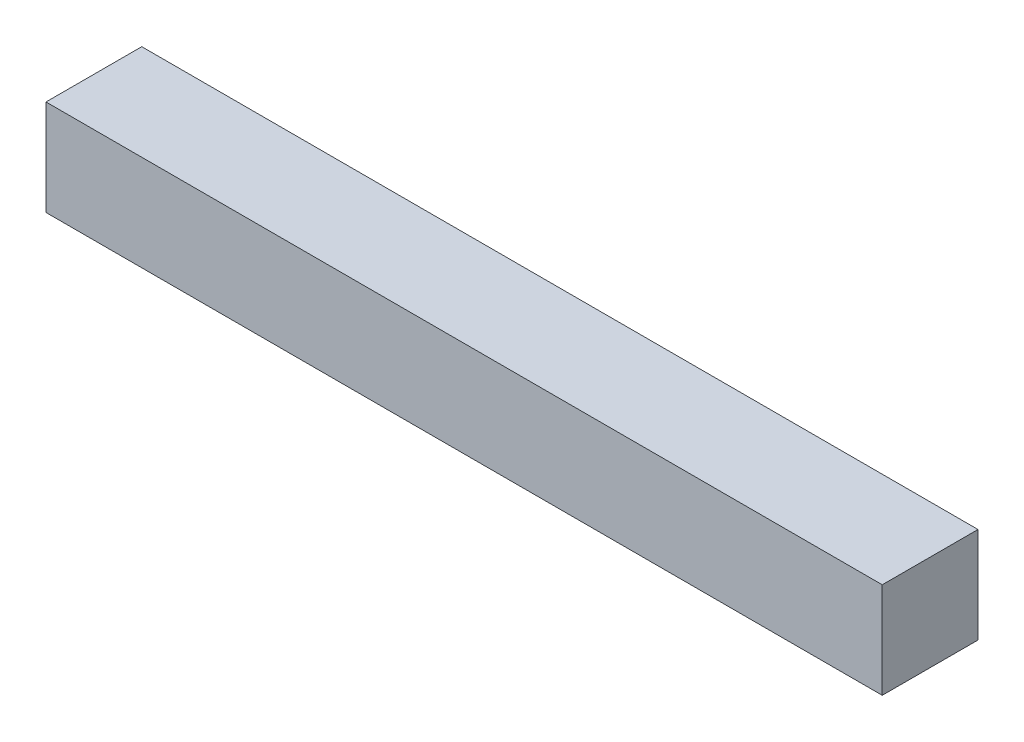
SolidWorks part; units mm, degrees
ref_plane "정면" through (0, 0, 0) normal (0, 0, 1) x (1, 0, 0)
ref_plane "윗면" through (0, 0, 0) normal (0, 1, 0) x (1, 0, 0)
ref_plane "우측면" through (0, 0, 0) normal (1, 0, 0) x (0, 0, -1)
sketch "스케치1" plane through (0, 0, 0) normal (0, 1, 0) x (1, 0, 0)
  line L1 (0, 0) -> (262, 0)
  line L2 (0, 0) -> (0, 30)
  line L3 (0, 30) -> (262, 30)
  line L4 (262, 0) -> (262, 30)
  dimension "D1" = 262
  dimension "D2" = 30
extrude "보스-돌출1" add sketch "스케치1" along normal blind 30
